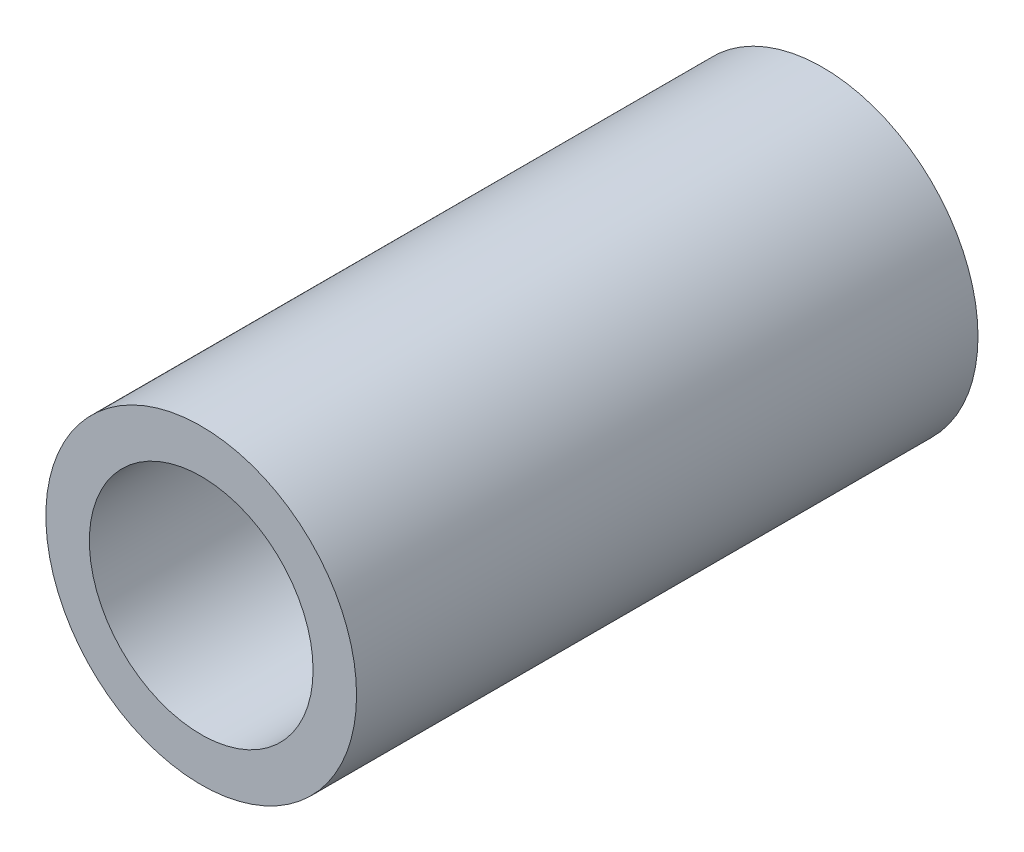
SolidWorks part; units mm, degrees
ref_plane "Front Plane" through (0, 0, 0) normal (0, 0, 1) x (1, 0, 0)
ref_plane "Top Plane" through (0, 0, 0) normal (0, 1, 0) x (1, 0, 0)
ref_plane "Right Plane" through (0, 0, 0) normal (1, 0, 0) x (0, 0, -1)
sketch "Sketch1" plane through (0, 0, 0) normal (0, 0, 1) x (1, 0, 0)
  line L0 (0, 1.143) -> (0, 1.5875) construction
  line L1 (0, -1.143) -> (0, -1.5875) construction
  circle A0 centre (0, 0) radius 1.5875
  circle A1 centre (0, 0) radius 1.143
  dimension "OD" = 3.175
  dimension "ID" = 2.286
sketch "Sketch2" plane through (0, 0, 0) normal (1, 0, 0) x (0, 0, -1)
  line L0 (-3.175, 1.143) -> (3.175, 1.143) construction
  line L1 (-3.175, -1.143) -> (3.175, -1.143) construction
  line L2 (-3.175, -1.5875) -> (3.175, -1.5875) construction
  line L3 (-3.175, 1.5875) -> (3.175, 1.5875) construction
  dimension "Length" = 6.35
extrude "Extrude1" add sketch "Sketch1" along normal up to vertex (3.175 mm away) and the other way up to vertex (3.175 mm away) up to point (0, 1.143, 3.175) other way up to point (0, 1.143, -3.175)
sketch "Sketch3" plane through (0, 0, 3.175) normal (0, 0, 1) x (1, 0, 0)
  circle A0 centre (0, 0) radius 1.143 construction
  circle A3 centre (0, 0) radius 1.143
  point P3 (-1.143, 0)
